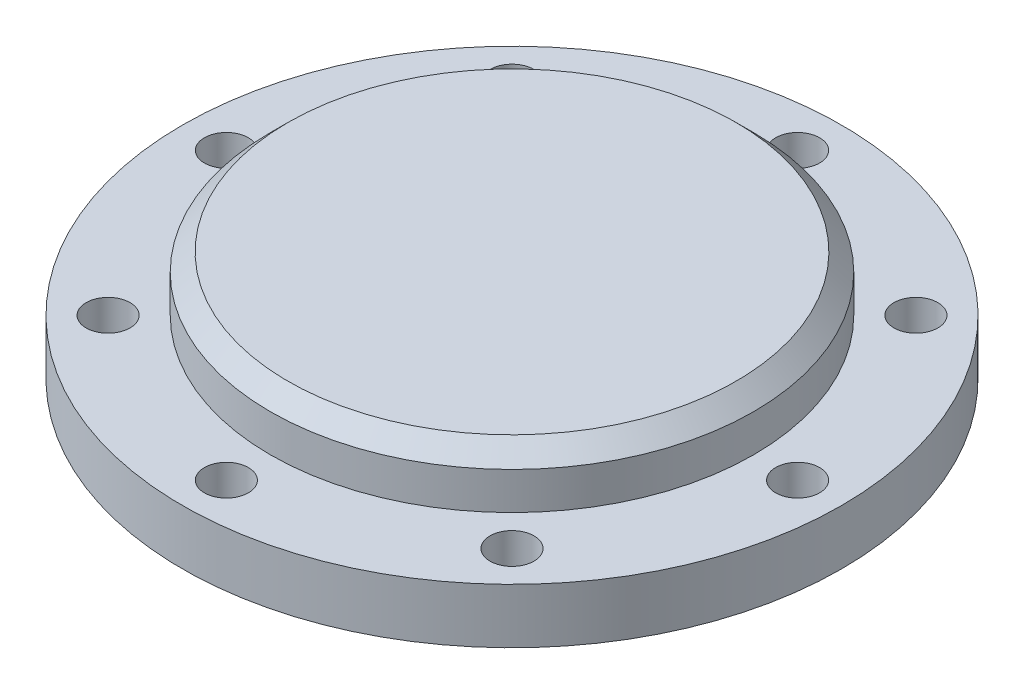
SolidWorks part; units mm, degrees
ref_plane "Спереди" through (0, 0, 0) normal (0, 0, 1) x (1, 0, 0)
ref_plane "Сверху" through (0, 0, 0) normal (0, 1, 0) x (1, 0, 0)
ref_plane "Справа" through (0, 0, 0) normal (1, 0, 0) x (0, 0, -1)
sketch "Эскиз1" plane through (0, 0, 0) normal (0, 0, 1) x (1, 0, 0)
  line L0 (-30, -10) -> (0, -10)
  line L3 (0, 0) -> (-20.4, 0)
  line L4 (-22, -1.6) -> (-22, -5)
  line L5 (-22, -5) -> (-30, -5)
  line L6 (-30, -5) -> (-30, -10)
  line L8 (0, 0) -> (0, -10)
  line L10 (-20.4, 0) -> (-22, -1.6)
  dimension "D1" = 22
  dimension "D2" = 30
  dimension "D3" = 10
  dimension "D4" = 5
  dimension "D5" = 45
  dimension "D6" = 1.6
revolve "Повернуть11" add sketch "Эскиз1" angle 360 about L8
sketch "Эскиз4" plane through (0, -5, 0) normal (0, 1, 0) x (1, 0, 0)
  circle A0 centre (0, 0) radius 26 construction
  circle A1 centre (0, 26) radius 2
  circle A2 centre (0, 0) radius 26 construction
  circle A3 centre (18.3848, 18.3848) radius 2
  circle A4 centre (0, 0) radius 26 construction
  circle A5 centre (26, 0) radius 2
  circle A6 centre (0, 0) radius 26 construction
  circle A7 centre (18.3848, -18.3848) radius 2
  circle A8 centre (0, 0) radius 26 construction
  circle A9 centre (0, -26) radius 2
  circle A10 centre (0, 0) radius 26 construction
  circle A11 centre (-18.3848, -18.3848) radius 2
  circle A12 centre (0, 0) radius 26 construction
  circle A13 centre (-26, 0) radius 2
  circle A14 centre (0, 0) radius 26 construction
  circle A15 centre (-18.3848, 18.3848) radius 2
  point P28 (0, 0)
  dimension "D1" = 4
  dimension "D2" = 8
extrude "Вырез-Вытянуть1" cut sketch "Эскиз4" against normal blind 20
